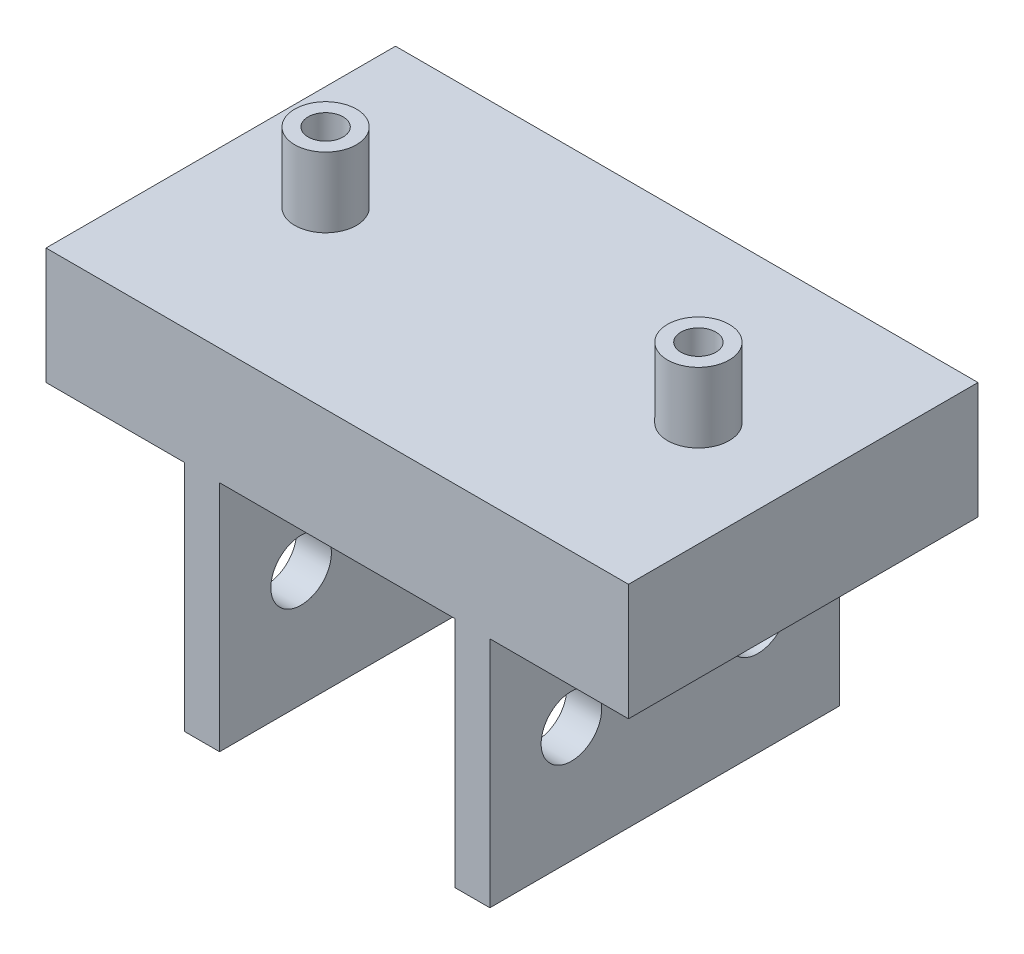
SolidWorks part; units mm, degrees
ref_plane "前视基准面" through (0, 0, 0) normal (0, 0, 1) x (1, 0, 0)
ref_plane "上视基准面" through (0, 0, 0) normal (0, 1, 0) x (1, 0, 0)
ref_plane "右视基准面" through (0, 0, 0) normal (1, 0, 0) x (0, 0, -1)
other "Configuration Table"
sketch "草图1" plane through (0, 0, 0) normal (0, 0, 1) x (1, 0, 0)
  line L0 (0, -5) -> (0, -29.7018) construction
  line L1 (-25, -5) -> (-13.1, -5)
  line L2 (-25, -5) -> (-25, 5)
  line L3 (-25, 5) -> (25, 5)
  line L4 (25, -5) -> (25, 5)
  line L5 (-25, -5) -> (25, 5) construction
  line L6 (-25, 5) -> (25, -5) construction
  line L8 (-13.1, -5) -> (-13.1, -25)
  line L9 (-13.1, -25) -> (-10.1, -25)
  line L10 (-10.1, -5) -> (-10.1, -25)
  line L12 (10.1, -5) -> (10.1, -25)
  line L13 (10.1, -25) -> (13.1, -25)
  line L14 (13.1, -5) -> (13.1, -25)
  line L15 (-10.1, -5) -> (10.1, -5)
  line L16 (13.1, -5) -> (25, -5)
  point P0 (0, 0)
  dimension "D1" = 50
  dimension "D2" = 10
  dimension "D3" = 3
  dimension "D4" = 20.2
  dimension "D5" = 20
extrude "凸台-拉伸1" add sketch "草图1" along normal blind 30
sketch "草图2" plane through (13.1, 0, 0) normal (1, 0, 0) x (0, 0, -1)
  line L0 (-30, -5) -> (0, -5) construction
  line L1 (0, -25) -> (0, -5) construction
  line L2 (-30, -25) -> (-30, -5) construction
  circle A0 centre (-23, -15) radius 2.6
  circle A1 centre (-7, -15) radius 2.6
  dimension "D3" = 5.2
  dimension "D4" = 5.2
  dimension "D1" = 10
  dimension "D2" = 7
  dimension "D5" = 7
extrude "切除-拉伸1" cut sketch "草图2" against normal through all
sketch "草图3" plane through (0, 5, 0) normal (0, 1, 0) x (1, 0, 0)
  line L0 (0, 0) -> (0, -30) construction
  line L1 (25, 0) -> (-25, 0) construction
  line L2 (-25, -15) -> (25, -15) construction
  line L3 (-25, -30) -> (-25, 0) construction
  line L4 (25, -30) -> (25, 0) construction
  line L5 (25, -30) -> (-25, -30) construction
  circle A0 centre (16, -15) radius 1.5
  circle A1 centre (-16, -15) radius 1.5
  dimension "D2" = 3
  dimension "D1" = 9
extrude "切除-拉伸2" cut sketch "草图3" against normal through all and the other way through all
sketch "草图4" plane through (13.1, 0, 0) normal (1, 0, 0) x (0, 0, -1)
  line L0 (-15, -25) -> (-15, -5) construction
  line L1 (-30, -25) -> (0, -25) construction
  line L2 (-30, -5) -> (0, -5) construction
  line L4 (-20, -11) -> (-10, -11)
  line L5 (-20, -11) -> (-20, -5)
  line L6 (-20, -5) -> (-10, -5)
  line L7 (-10, -11) -> (-10, -5)
  line L8 (-20, -11) -> (-10, -5) construction
  line L9 (-20, -5) -> (-10, -11) construction
  point P6 (-15, -8)
  dimension "D1" = 10
  dimension "D2" = 6
extrude "切除-拉伸3" cut sketch "草图4" against normal through all
sketch "草图5" plane through (0, 5, 0) normal (0, 1, 0) x (1, 0, 0)
  circle A0 centre (16, -15) radius 2.65
  circle A1 centre (16, -15) radius 1.5
  circle A2 centre (-16, -15) radius 1.5
  circle A3 centre (-16, -15) radius 2.65
  dimension "D1" = 5.3
  dimension "D2" = 5.3
extrude "凸台-拉伸2" add sketch "草图5" along normal blind 6
